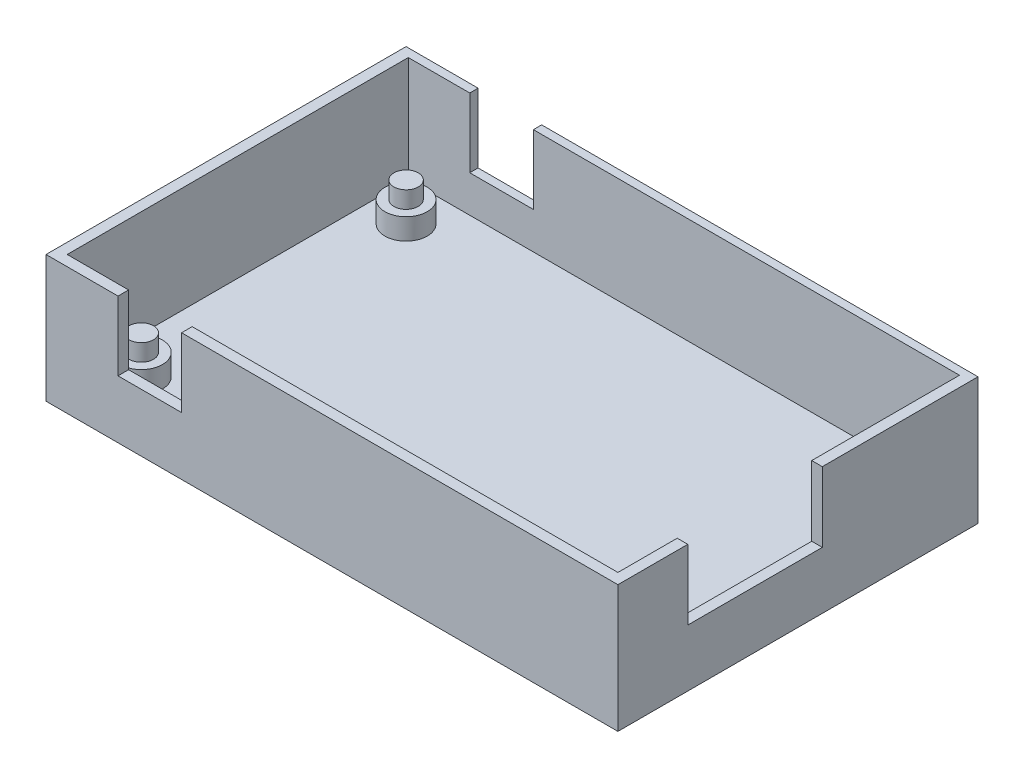
SolidWorks part; units mm, degrees
ref_plane "Front Plane" through (0, 0, 0) normal (0, 0, 1) x (1, 0, 0)
ref_plane "Top Plane" through (0, 0, 0) normal (0, 1, 0) x (1, 0, 0)
ref_plane "Right Plane" through (0, 0, 0) normal (1, 0, 0) x (0, 0, -1)
sketch "Sketch1" plane through (0, 0, 0) normal (0, 1, 0) x (1, 0, 0)
  line L1 (0, 0) -> (68.58, 0)
  line L2 (0, 0) -> (0, 43.18)
  line L3 (0, 43.18) -> (68.58, 43.18)
  line L4 (68.58, 0) -> (68.58, 43.18)
  point P13 (34.29, 43.18)
  point P14 (0, 21.59)
  dimension "D1" = 43.18
  dimension "D2" = 68.58
extrude "Boss-Extrude1" add sketch "Sketch1" along normal blind 2.54
sketch "Sketch5" plane through (0, 2.54, 0) normal (0, 1, 0) x (1, 0, 0)
  line L0 (68.58, 43.18) -> (0, 43.18) construction
  line L1 (68.58, 43.18) -> (0, 43.18) construction
  line L2 (0, 43.18) -> (0, 0) construction
  circle A0 centre (5.715, 37.465) radius 2.54
  circle A1 centre (62.865, 37.465) radius 2.54
  circle A2 centre (5.715, 5.715) radius 2.54
  circle A3 centre (62.865, 5.715) radius 2.54
  point P8 (34.29, 43.18)
  point P11 (34.29, 43.18)
  point P15 (34.29, 43.18)
  point P16 (34.29, 43.18)
  point P17 (0, 21.59)
  point P20 (0, 21.59)
  point P21 (0, 21.59)
  point P22 (0, 21.59)
  dimension "D1" = 5.08
  dimension "D2" = 5.08
  dimension "D3" = 5.08
  dimension "D4" = 5.08
  dimension "D5" = 28.575
  dimension "D6" = 28.575
  dimension "D7" = 28.575
  dimension "D8" = 15.875
  dimension "D9" = 28.575
  dimension "D10" = 15.875
  dimension "D11" = 15.875
  dimension "D12" = 15.875
extrude "Boss-Extrude2" add sketch "Sketch5" along normal blind 2.54
sketch "Sketch6" plane through (0, 2.54, 0) normal (0, 1, 0) x (1, 0, 0)
  line L0 (0, 43.18) -> (0, 0)
  line L1 (0, 0) -> (68.58, 0)
  line L2 (68.58, 0) -> (68.58, 43.18)
  line L3 (68.58, 43.18) -> (0, 43.18)
  line L4 (1.27, 42.1719) -> (1.27, 1.27)
  line L5 (1.27, 1.27) -> (67.31, 1.27)
  line L6 (67.31, 1.27) -> (67.31, 42.2296)
  line L7 (67.31, 42.2296) -> (1.27, 42.1719)
  dimension "D1" = 1.27
  dimension "D2" = 1.27
  dimension "D3" = 1.27
  dimension "D4" = 0.05
extrude "Boss-Extrude3" add sketch "Sketch6" along normal blind 12.7
sketch "Sketch7" plane through (0, 5.08, 0) normal (0, 1, 0) x (1, 0, 0)
  circle A0 centre (5.715, 37.465) radius 1.4605
  circle A1 centre (5.715, 5.715) radius 1.4605
  circle A2 centre (62.865, 5.715) radius 1.4605
  circle A3 centre (62.865, 37.465) radius 1.4605
  dimension "D1" = 2.921
  dimension "D2" = 2.921
  dimension "D3" = 2.921
  dimension "D4" = 2.921
extrude "Boss-Extrude4" add sketch "Sketch7" along normal blind 2.032
sketch "Sketch8" plane through (0, 0, 0) normal (0, 0, 1) x (1, 0, 0)
  line L0 (0, 15.24) -> (68.58, 15.24) construction
  line L1 (8.636, 15.24) -> (16.256, 15.24)
  line L2 (8.636, 15.24) -> (8.636, 6.9544)
  line L3 (8.636, 6.9544) -> (16.256, 6.9544)
  line L4 (16.256, 15.24) -> (16.256, 6.9544)
  line L5 (0, 15.24) -> (0, 0) construction
  dimension "D1" = 8.636
  dimension "D2" = 7.62
  dimension "D3" = 8.2856
extrude "Cut-Extrude1" cut sketch "Sketch8" against normal through all
sketch "Sketch9" plane through (68.58, 0, 0) normal (1, 0, 0) x (0, 0, -1)
  line L0 (0, 15.24) -> (43.18, 15.24) construction
  line L1 (8.382, 15.24) -> (24.511, 15.24)
  line L2 (8.382, 15.24) -> (8.382, 6.858)
  line L3 (8.382, 6.858) -> (24.511, 6.858)
  line L4 (24.511, 15.24) -> (24.511, 6.858)
  line L5 (0, 15.24) -> (0, 0) construction
  dimension "D1" = 24.511
  dimension "D2" = 8.382
  dimension "D3" = 8.382
extrude "Cut-Extrude2" cut sketch "Sketch9" against normal blind 2.032
